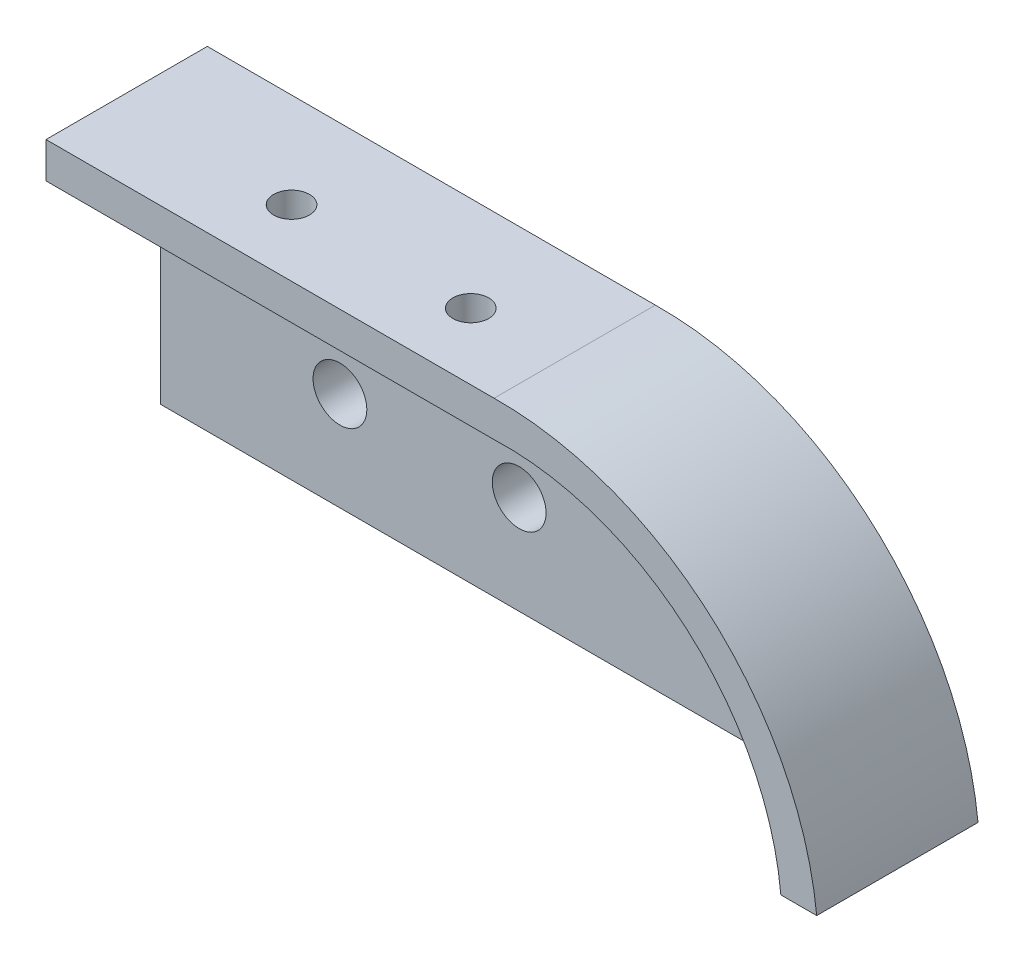
SolidWorks part; units mm, degrees
ref_plane "Alzado" through (0, 0, 0) normal (0, 0, 1) x (1, 0, 0)
ref_plane "Planta" through (0, 0, 0) normal (0, 1, 0) x (1, 0, 0)
ref_plane "Vista lateral" through (0, 0, 0) normal (1, 0, 0) x (0, 0, -1)
ref_plane "Plano1" through (0, 0, 4.5) normal (0, 0, 1) x (1, 0, 0)
sketch "Croquis1" plane through (0, 0, 4.5) normal (0, 0, 1) x (1, 0, 0)
  line L0 (0, 8) -> (0, 0)
  line L1 (0, 0) -> (21.5, 0)
  line L2 (12.5, 8) -> (0, 8)
  arc A0 (21.5, 0) -> (12.5, 8) centre (12.6198, -0.9277) ccw
extrude "Saliente-Extruir1" add sketch "Croquis1" against normal blind 4.5
sketch "Croquis2" plane through (0, 0, 4.5) normal (0, 0, 1) x (1, 0, 0)
  line L0 (12.5, 7) -> (0, 7)
  line L1 (0, 7) -> (0, 0)
  line L2 (0, 0) -> (20.5, 0)
  arc A0 (20.5, 0) -> (12.5, 7) centre (12.7987, -0.7301) ccw
extrude "Cortar-Extruir1" cut sketch "Croquis2" against normal blind 3.2
hole_wizard "Diámetro de taladro Ø1.0 (1)1" positions "Croquis4" profile "Croquis3" hole size "Ø1.0" standard "Ansi Metric"
sketch "Croquis4" plane through (0, 8, 0) normal (0, 1, 0) x (1, 0, 0)
  point P0 (5, -2.65)
  point P1 (10, -2.65)
sketch "Croquis3" plane through (5, 8, 2.65) normal (1, 0, 0) x (0, 0, 1)
  line L0 (0, 0) -> (0, 8)
  line L1 (0, 8) -> (0.5, 8)
  line L2 (0.5, 8) -> (0.5, 0)
  line L5 (0.5, 0) -> (0, 0)
  line L11 (0, -6.35) -> (0, 107.95) construction
  dimension "Diámetro de taladro hasta el siguiente" = 1
  dimension "Profundidad de taladro hasta el siguiente" = 8
hole_wizard "Diámetro de taladro Ø1.5 (1.5)1" positions "Croquis6" profile "Croquis5" hole size "Ø1.5" standard "Ansi Metric"
sketch "Croquis6" plane through (0, 0, 1.3) normal (0, 0, 1) x (1, 0, 0)
  point P0 (10, 2.75)
  point P1 (5, 2.75)
sketch "Croquis5" plane through (10, 2.75, 1.3) normal (1, 0, 0) x (0, -1, 0)
  line L0 (0, 0) -> (0, 1.3)
  line L1 (0, 1.3) -> (0.75, 1.3)
  line L2 (0.75, 1.3) -> (0.75, 0)
  line L5 (0.75, 0) -> (0, 0)
  line L11 (0, -6.35) -> (0, 107.95) construction
  dimension "Diámetro de taladro hasta el siguiente" = 1.5
  dimension "Profundidad de taladro hasta el siguiente" = 1.3
